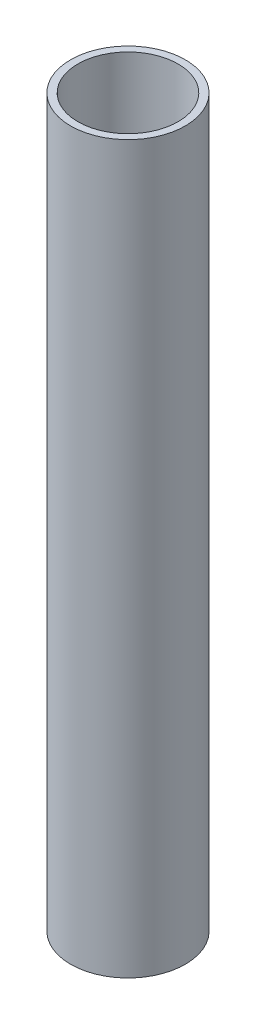
SolidWorks part; units mm, degrees
ref_plane "Front Plane" through (0, 0, 0) normal (0, 0, 1) x (1, 0, 0)
ref_plane "Top Plane" through (0, 0, 0) normal (0, 1, 0) x (1, 0, 0)
ref_plane "Right Plane" through (0, 0, 0) normal (1, 0, 0) x (0, 0, -1)
sketch "Sketch1" plane through (0, 0, 0) normal (0, 1, 0) x (1, 0, 0)
  circle A0 centre (0, 0) radius 7.9
  dimension "D1" = 15.8
extrude "Boss-Extrude1" add sketch "Sketch1" along normal blind 100
sketch "Sketch2" plane through (0, 100, 0) normal (0, 1, 0) x (1, 0, 0)
  circle A0 centre (0, 0) radius 6.9
  circle A1 centre (0, 0) radius 7.9 construction
  dimension "D1" = 1
extrude "Cut-Extrude1" cut sketch "Sketch2" against normal blind 99
